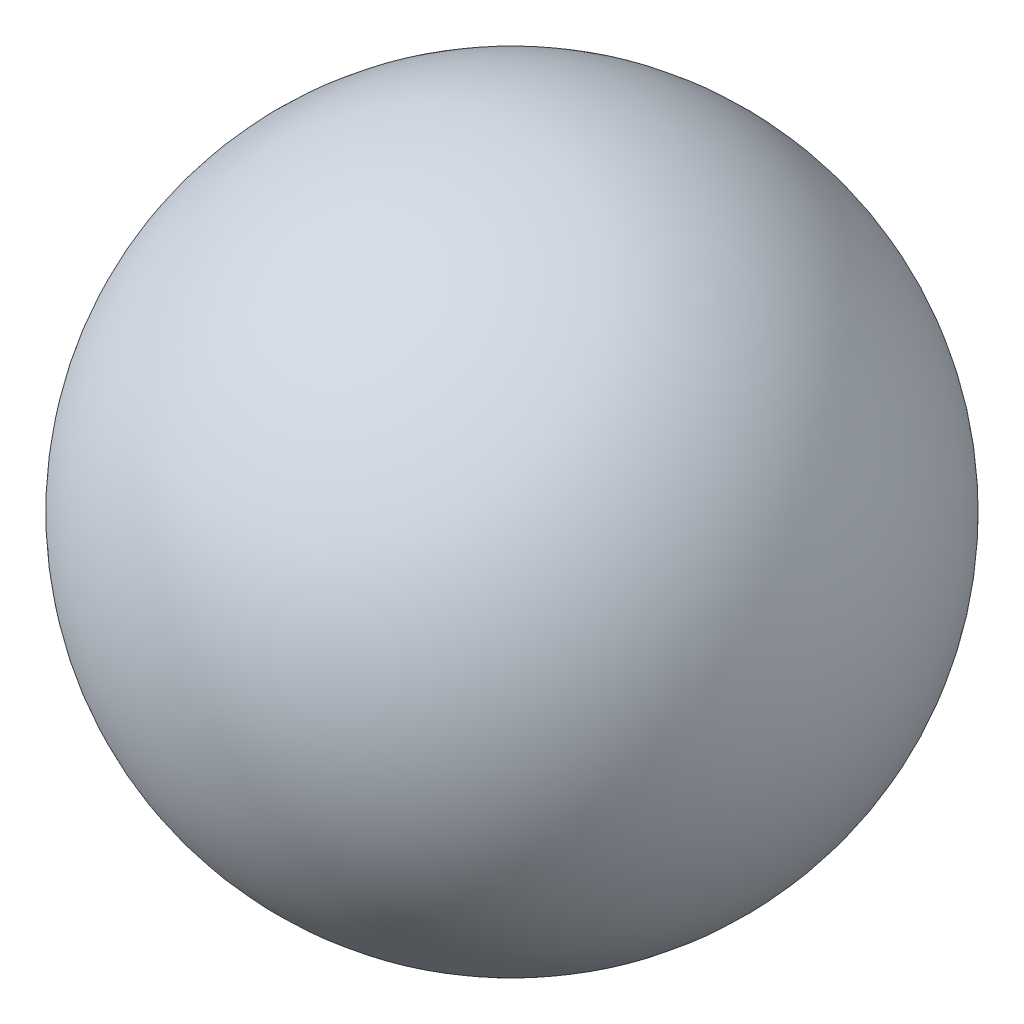
SolidWorks part; units mm, degrees
ref_plane "前视基准面" through (0, 0, 0) normal (0, 0, 1) x (1, 0, 0)
ref_plane "上视基准面" through (0, 0, 0) normal (0, 1, 0) x (1, 0, 0)
ref_plane "右视基准面" through (0, 0, 0) normal (1, 0, 0) x (0, 0, -1)
other "Configuration Table"
sketch "草图1" plane through (0, 0, 0) normal (0, 0, 1) x (1, 0, 0)
  line L0 (0, 0) -> (0, 8.5)
  line L1 (0, 0) -> (0, -8.5)
  arc A0 (0, -8.5) -> (0, 8.5) centre (0, 0) ccw
  dimension "D1" = 17
revolve "旋转3" add sketch "草图1" angle 360 about L0
